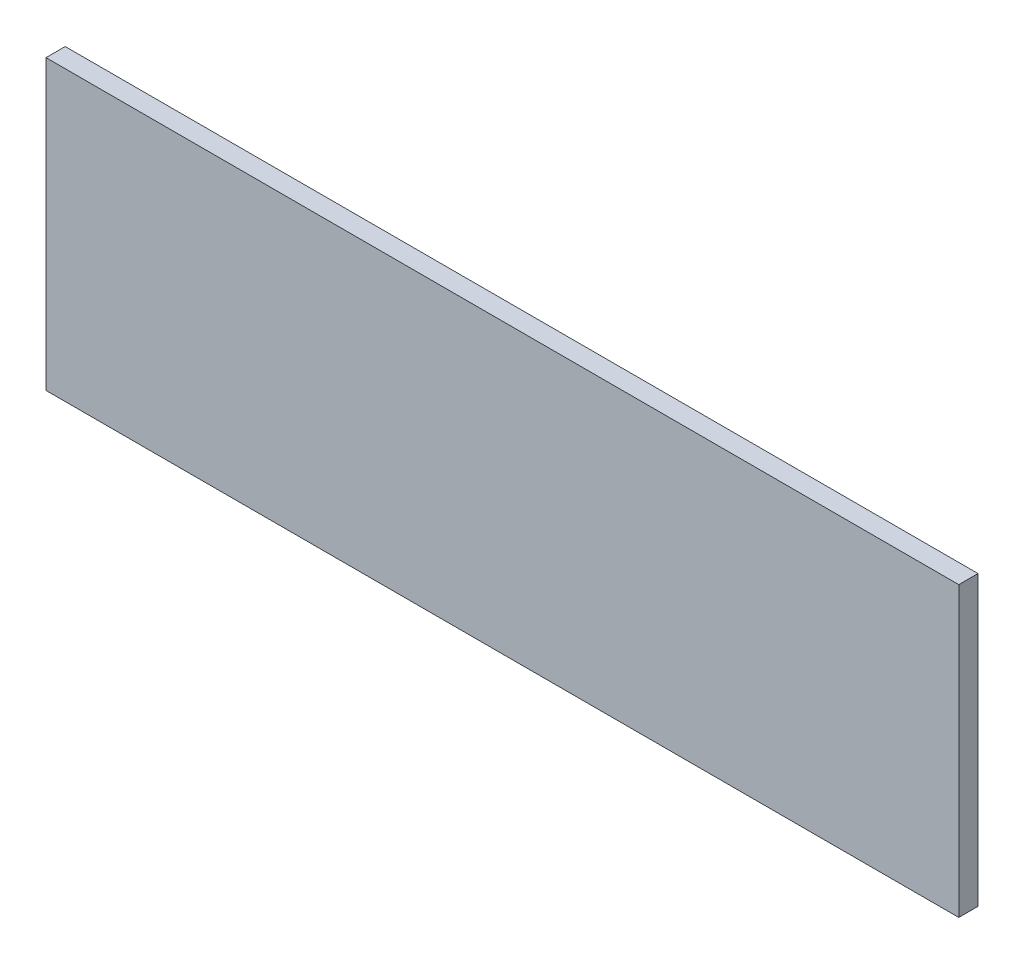
SolidWorks part; units mm, degrees
ref_plane "Alzado" through (0, 0, 0) normal (0, 0, 1) x (1, 0, 0)
ref_plane "Planta" through (0, 0, 0) normal (0, 1, 0) x (1, 0, 0)
ref_plane "Vista lateral" through (0, 0, 0) normal (1, 0, 0) x (0, 0, -1)
sketch "Croquis1" plane through (0, 0, 0) normal (0, 0, 1) x (1, 0, 0)
  line L1 (0, 0) -> (190, 0)
  line L2 (0, 0) -> (0, 60)
  line L3 (0, 60) -> (190, 60)
  line L4 (190, 0) -> (190, 60)
  dimension "D1" = 60
  dimension "D2" = 190
extrude "Saliente-Extruir1" add sketch "Croquis1" along normal mid plane 4
